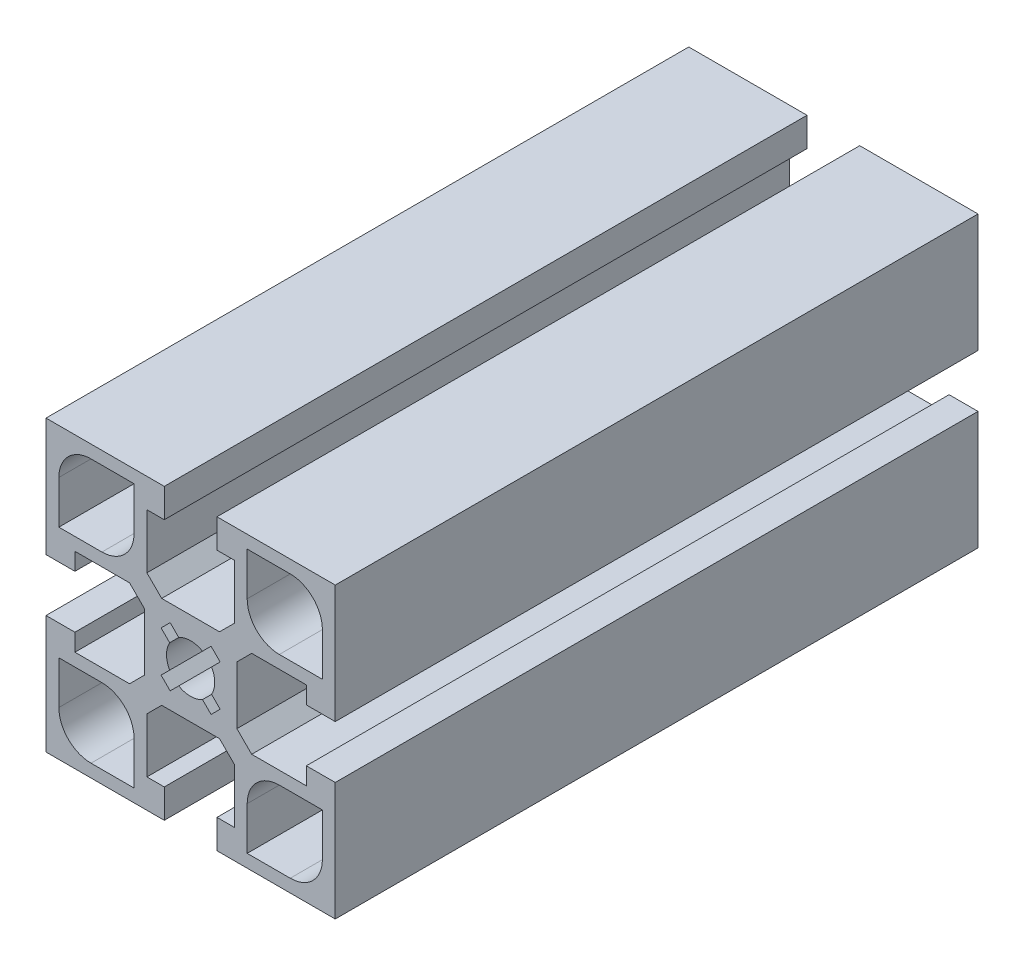
SolidWorks part; units mm, degrees
material "6061 Alloy"
ref_plane "Front Plane" through (0, 0, 0) normal (0, 0, 1) x (1, 0, 0)
ref_plane "Top Plane" through (0, 0, 0) normal (0, 1, 0) x (1, 0, 0)
ref_plane "Right Plane" through (0, 0, 0) normal (1, 0, 0) x (0, 0, -1)
sketch "Sketch1" plane through (0, 0, 0) normal (0, 0, 1) x (1, 0, 0)
  line L4 (-20.5, 8.8) -> (-20.5, 15.5)
  line L5 (-13.8, 8.8) -> (-20.5, 8.8)
  line L6 (-8.8, 20.5) -> (-8.8, 13.8)
  line L7 (-15.5, 20.5) -> (-8.8, 20.5)
  line L12 (20.5, 8.8) -> (13.8, 8.8)
  line L13 (20.5, 15.5) -> (20.5, 8.8)
  line L14 (8.8, 20.5) -> (15.5, 20.5)
  line L15 (8.8, 13.8) -> (8.8, 20.5)
  line L20 (15.5, -20.5) -> (8.8, -20.5)
  line L21 (20.5, -8.8) -> (20.5, -15.5)
  line L22 (13.8, -8.8) -> (20.5, -8.8)
  line L23 (8.8, -20.5) -> (8.8, -13.8)
  line L28 (-8.8, -20.5) -> (-15.5, -20.5)
  line L29 (-8.8, -13.8) -> (-8.8, -20.5)
  line L30 (-20.5, -8.8) -> (-13.8, -8.8)
  line L31 (-20.5, -15.5) -> (-20.5, -8.8)
  line L88 (-18, -6.8) -> (-18, -4.1)
  line L89 (-18, -4.1) -> (-22.5, -4.1)
  line L90 (-22.5, -4.1) -> (-22.5, -22.5)
  line L91 (-22.5, -22.5) -> (-4.1, -22.5)
  line L92 (-4.1, -22.5) -> (-4.1, -18)
  line L93 (-4.1, -18) -> (-6.8, -18)
  line L94 (-6.8, -18) -> (-6.8, -9.5)
  line L95 (-6.8, -9.5) -> (-4.5, -7.2)
  line L96 (-4.5, -7.2) -> (4.5, -7.2)
  line L97 (4.5, -7.2) -> (6.8, -9.5)
  line L98 (6.8, -9.5) -> (6.8, -18)
  line L99 (6.8, -18) -> (4.1, -18)
  line L100 (4.1, -18) -> (4.1, -22.5)
  line L101 (4.1, -22.5) -> (22.5, -22.5)
  line L102 (22.5, -22.5) -> (22.5, -4.1)
  line L103 (22.5, -4.1) -> (18, -4.1)
  line L104 (18, -4.1) -> (18, -6.8)
  line L105 (18, -6.8) -> (9.5, -6.8)
  line L106 (9.5, -6.8) -> (7.2, -4.5)
  line L107 (7.2, -4.5) -> (7.2, 4.5)
  line L108 (7.2, 4.5) -> (9.5, 6.8)
  line L109 (9.5, 6.8) -> (18, 6.8)
  line L110 (18, 6.8) -> (18, 4.1)
  line L111 (18, 4.1) -> (22.5, 4.1)
  line L112 (22.5, 4.1) -> (22.5, 22.5)
  line L113 (22.5, 22.5) -> (4.1, 22.5)
  line L114 (4.1, 22.5) -> (4.1, 18)
  line L115 (4.1, 18) -> (6.8, 18)
  line L116 (6.8, 18) -> (6.8, 9.5)
  line L117 (6.8, 9.5) -> (4.5, 7.2)
  line L118 (4.5, 7.2) -> (-4.5, 7.2)
  line L119 (-4.5, 7.2) -> (-6.8, 9.5)
  line L120 (-6.8, 9.5) -> (-6.8, 18)
  line L121 (-6.8, 18) -> (-4.1, 18)
  line L122 (-4.1, 18) -> (-4.1, 22.5)
  line L123 (-4.1, 22.5) -> (-22.5, 22.5)
  line L124 (-22.5, 22.5) -> (-22.5, 4.1)
  line L125 (-22.5, 4.1) -> (-18, 4.1)
  line L126 (-18, 4.1) -> (-18, 6.8)
  line L127 (-18, 6.8) -> (-9.5, 6.8)
  line L128 (-9.5, 6.8) -> (-7.2, 4.5)
  line L129 (-7.2, 4.5) -> (-7.2, -4.5)
  line L130 (-7.2, -4.5) -> (-9.5, -6.8)
  line L131 (-9.5, -6.8) -> (-18, -6.8)
  line L132 (-3.2627, 1.8485) -> (-4.5962, 3.182)
  line L133 (-4.5962, -3.182) -> (-3.2627, -1.8485)
  line L134 (-3.182, -4.5962) -> (-4.5962, -3.182)
  line L135 (-1.8485, -3.2627) -> (-3.182, -4.5962)
  line L136 (3.182, -4.5962) -> (1.8485, -3.2627)
  line L137 (4.5962, -3.182) -> (3.182, -4.5962)
  line L138 (3.2627, -1.8485) -> (4.5962, -3.182)
  line L139 (4.5962, 3.182) -> (3.2627, 1.8485)
  line L140 (3.182, 4.5962) -> (4.5962, 3.182)
  line L141 (1.8485, 3.2627) -> (3.182, 4.5962)
  line L142 (-3.182, 4.5962) -> (-1.8485, 3.2627)
  line L143 (-4.5962, 3.182) -> (-3.182, 4.5962)
  arc A2 (-13.8, 8.8) -> (-8.8, 13.8) centre (-13.8, 13.8) ccw
  arc A3 (-15.5, 20.5) -> (-20.5, 15.5) centre (-15.5, 15.5) ccw
  arc A6 (8.8, 13.8) -> (13.8, 8.8) centre (13.8, 13.8) ccw
  arc A7 (20.5, 15.5) -> (15.5, 20.5) centre (15.5, 15.5) ccw
  arc A10 (15.5, -20.5) -> (20.5, -15.5) centre (15.5, -15.5) ccw
  arc A11 (13.8, -8.8) -> (8.8, -13.8) centre (13.8, -13.8) ccw
  arc A14 (-20.5, -15.5) -> (-15.5, -20.5) centre (-15.5, -15.5) ccw
  arc A15 (-8.8, -13.8) -> (-13.8, -8.8) centre (-13.8, -13.8) ccw
  arc A20 (-3.2627, 1.8485) -> (-3.2627, -1.8485) centre (0, 0) ccw
  arc A21 (-1.8485, -3.2627) -> (1.8485, -3.2627) centre (0, 0) ccw
  arc A22 (3.2627, -1.8485) -> (3.2627, 1.8485) centre (0, 0) ccw
  arc A23 (1.8485, 3.2627) -> (-1.8485, 3.2627) centre (0, 0) ccw
extrude "Boss-Extrude1" add sketch "Sketch1" along normal blind 100
